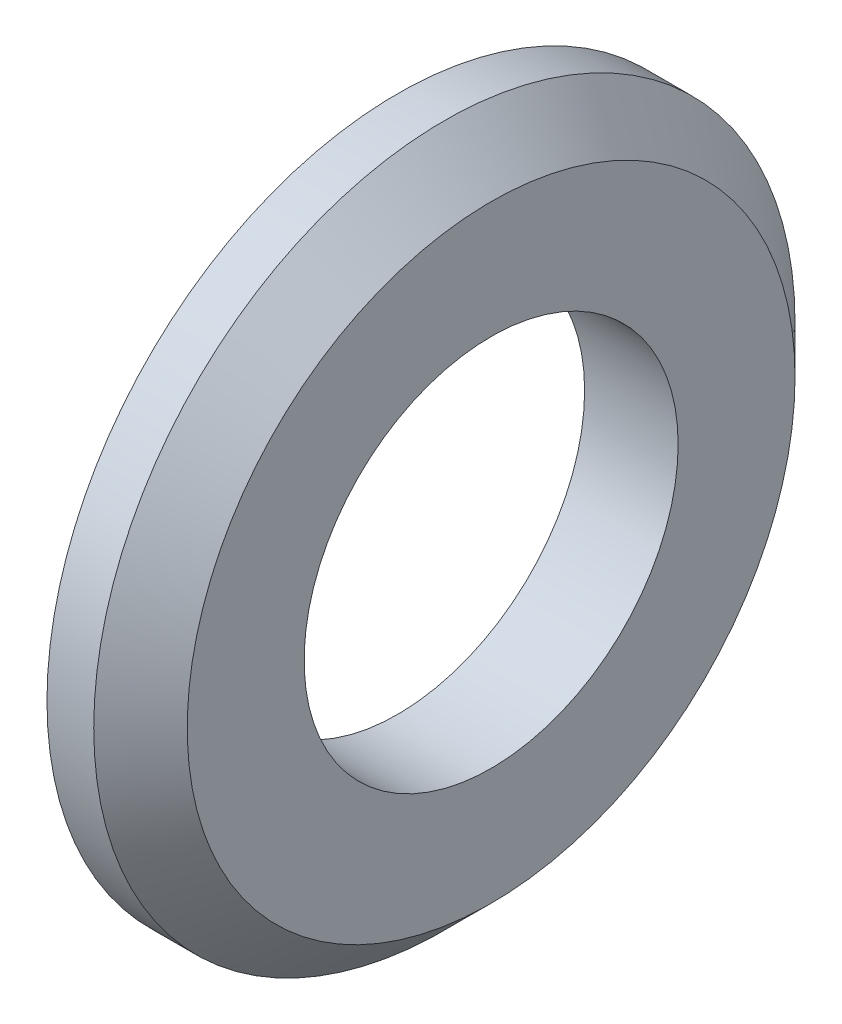
SolidWorks part; units mm, degrees
material "AISI 1020"
ref_plane "Front Plane" through (0, 0, 0) normal (0, 0, 1) x (1, 0, 0)
ref_plane "Top Plane" through (0, 0, 0) normal (0, 1, 0) x (1, 0, 0)
ref_plane "Right Plane" through (0, 0, 0) normal (1, 0, 0) x (0, 0, -1)
sketch "Sketch1" plane through (0, 0, 0) normal (1, 0, 0) x (0, 0, -1)
  circle A0 centre (0, 0) radius 6
  circle A1 centre (0, 0) radius 3.2
  dimension "Vidinis d" = 6.4
  dimension "Isorinis d" = 12
extrude "Extrude1" add sketch "Sketch1" along normal blind 1.6
chamfer "Chamfer1" distance 0.8 angle 45 1 edges at (1.6, 0, -6)
equation "\"D1@Chamfer1\" = \"Storis@Extrude1\" / 2"
